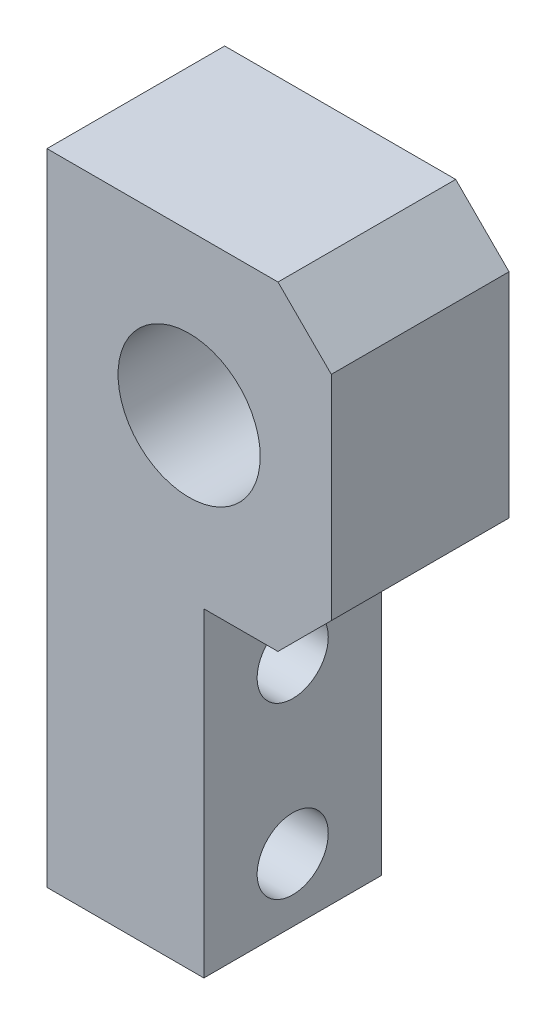
SolidWorks part; units mm, degrees
ref_plane "Спереди" through (0, 0, 0) normal (0, 0, 1) x (1, 0, 0)
ref_plane "Сверху" through (0, 0, 0) normal (0, 1, 0) x (1, 0, 0)
ref_plane "Справа" through (0, 0, 0) normal (1, 0, 0) x (0, 0, -1)
sketch "Эскиз1" plane through (0, 0, 0) normal (1, 0, 0) x (0, 0, -1)
  line L0 (-20, -40.6306) -> (-68.5325, -40.6306) construction
  line L1 (-20, -22.6306) -> (-10, -22.6306)
  line L2 (-20, -22.6306) -> (-20, -58.6306)
  line L3 (-20, -58.6306) -> (-10, -58.6306)
  line L4 (-10, -22.6306) -> (-10, -58.6306)
  point P0 (0, 0)
  dimension "D1" = 18
  dimension "D2" = 18
extrude "Вытянуть1" add sketch "Эскиз1" along normal blind 16
sketch "Эскиз5" plane through (0, 0, 20) normal (0, 0, 1) x (1, 0, 0)
  line L0 (0, -22.6306) -> (0, -58.6306) construction
  line L1 (16, -22.6306) -> (0, -22.6306) construction
  circle A0 centre (8, -31.6306) radius 4
  dimension "D1" = 8
  dimension "D2" = 9
extrude "Вырез-Вытянуть2" cut sketch "Эскиз5" against normal through all
sketch "Эскиз6" plane through (0, 0, 20) normal (0, 0, 1) x (1, 0, 0)
  line L0 (16, -40.6306) -> (30.1349, -40.6306) construction
  line L7 (16, -22.6306) -> (16, -58.6306) construction
  line L8 (16, -40.6306) -> (16, -58.6306)
  line L9 (8.8286, -40.6397) -> (8.8286, -58.6306)
  line L10 (8.8286, -58.6306) -> (16, -58.6306)
  line L11 (16, -40.6306) -> (8.8286, -40.6397)
  point P1 (16, -40.6306)
  point P16 (22.8286, -40.6306)
extrude "Вырез-Вытянуть3" cut sketch "Эскиз6" against normal through all
chamfer "Фаска1" distance 3 angle 45 2 edges at (16, -40.6306, 15) (16, -22.6306, 15)
sketch "Эскиз7" plane through (8.8286, 0, 0) normal (1, 0, 0) x (0, 0, -1)
  line L0 (-15, -58.6306) -> (-15, -45.3217) construction
  circle A0 centre (-15, -55.0758) radius 2
  circle A1 centre (-15, -45.5133) radius 2
extrude "Вытянуть2" cut sketch "Эскиз7" against normal through all
